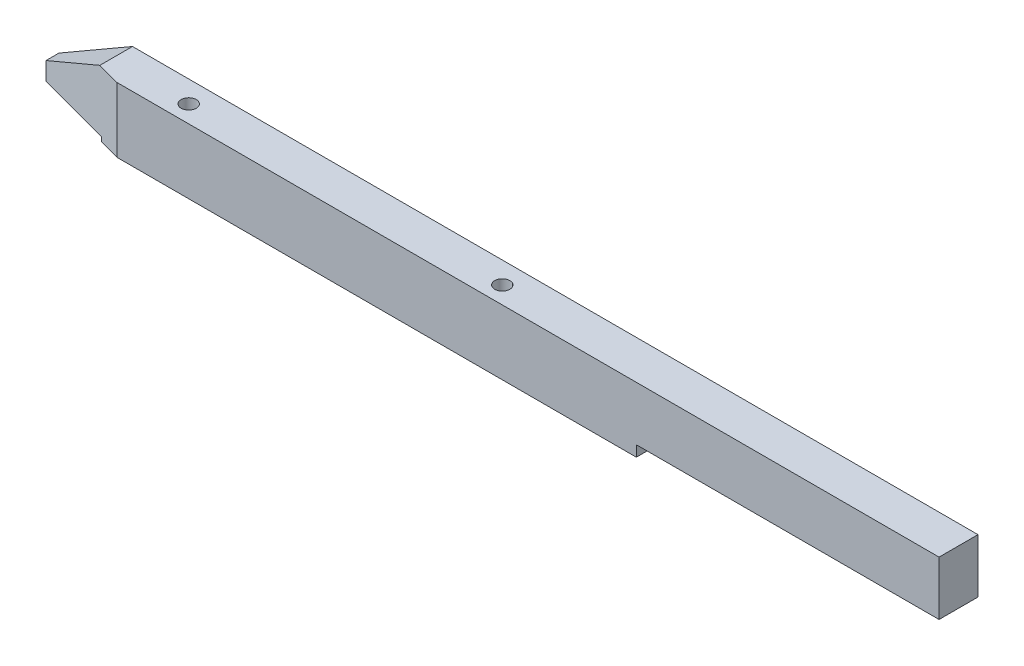
SolidWorks part; units mm, degrees
material "PE1000 hellgrau"
ref_plane "Vorne" through (0, 0, 0) normal (0, 0, 1) x (1, 0, 0)
ref_plane "Oben" through (0, 0, 0) normal (0, 1, 0) x (1, 0, 0)
ref_plane "Rechts" through (0, 0, 0) normal (1, 0, 0) x (0, 0, -1)
sketch "Skizze1" plane through (0, 0, 0) normal (1, 0, 0) x (0, 0, -1)
  line L1 (-9, 15) -> (9, 15)
  line L2 (-9, 15) -> (-9, -15)
  line L3 (-9, -15) -> (9, -15)
  line L4 (9, 15) -> (9, -15)
  line L5 (-9, 15) -> (9, -15) construction
  line L6 (-9, -15) -> (9, 15) construction
  point P0 (0, 0)
  dimension "D1" = 18
  dimension "D2" = 30
extrude "Aufsatz-Linear austragen1" add sketch "Skizze1" along normal mid plane 425
chamfer "Fase1" distance 12 angle 75 1 edges at (-212.5, 0, 9)
hole_wizard "Ø7.0 (7) Durchmesser Bohrung1" positions "Skizze3" profile "Skizze2" hole size "Ø7.0" standard "Gabler-Normteile" end condition through all
sketch "Skizze3" plane through (0, 15, 0) normal (0, 1, 0) x (1, 0, 0)
  line L0 (-212.5, 9) -> (-212.5, 3) construction
  line L1 (212.5, 9) -> (-212.5, 9) construction
  point P0 (-142.5, -1)
  point P2 (2.5, -1)
other "AusrichtungGruppe1" parameters "D1"=0, "D2"=70, "D3"=215, "D4"=465
sketch "Skizze2" plane through (-142.5, 15, 1) normal (1, 0, 0) x (0, 0, 1)
  line L0 (0, 0) -> (0, 30)
  line L1 (0, 30) -> (3.5, 30)
  line L2 (3.5, 30) -> (3.5, 0)
  line L5 (3.5, 0) -> (0, 0)
  line L11 (0, -6.35) -> (0, 107.95) construction
  dimension "Bohrerdurchmesser" = 7
  dimension "Bohrungstiefe" = 30
sketch "Skizze4" plane through (0, 0, 9) normal (0, 0, 1) x (1, 0, 0)
  line L0 (-212.5, -15) -> (-212.5, 15) construction
  line L1 (212.5, -15) -> (72.5, -15)
  line L2 (212.5, -15) -> (212.5, -10)
  line L3 (212.5, -10) -> (72.5, -10)
  line L4 (72.5, -15) -> (72.5, -10)
  line L5 (-212.5, -13) -> (-177.5, -13)
  line L6 (-212.5, -13) -> (-212.5, -15)
  line L7 (-212.5, -15) -> (-177.5, -15)
  line L8 (-177.5, -13) -> (-177.5, -15)
  line L9 (-167.7154, -15) -> (-212.5, -15) construction
  dimension "D1" = 5
  dimension "D2" = 140
  dimension "D3" = 35
  dimension "D4" = 2
extrude "Schnitt-Linear austragen1" cut sketch "Skizze4" against normal through all
sketch "Skizze5" plane through (0, 0, 9) normal (0, 0, 1) x (1, 0, 0)
  line L0 (-178.5, 15) -> (-212.5, 15)
  line L1 (212.5, 15) -> (-167.7154, 15) construction
  line L2 (-212.5, -4.6299) -> (-212.5, 15)
  line L3 (-212.5, -13) -> (-212.5, 15) construction
  line L4 (-212.5, -4.6299) -> (-178.5, 15)
  dimension "D2" = 30
  dimension "D3" = 34
extrude "Schnitt-Linear austragen2" cut sketch "Skizze5" against normal through all
